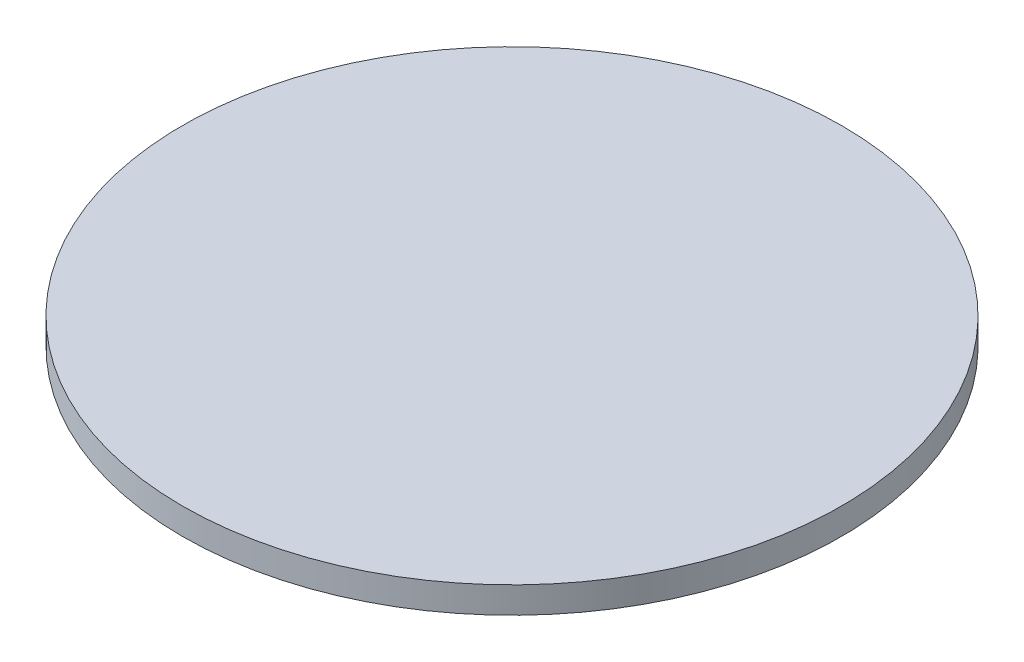
SolidWorks part; units mm, degrees
ref_plane "Front Plane" through (0, 0, 0) normal (0, 0, 1) x (1, 0, 0)
ref_plane "Top Plane" through (0, 0, 0) normal (0, 1, 0) x (1, 0, 0)
ref_plane "Right Plane" through (0, 0, 0) normal (1, 0, 0) x (0, 0, -1)
sketch "Sketch1" plane through (0, 0, 0) normal (0, 1, 0) x (1, 0, 0)
  circle A0 centre (0, 0) radius 12.5
  point P0 (0, 0)
  dimension "D3" = 25
extrude "Boss-Extrude1" add sketch "Sketch1" along normal blind 1
